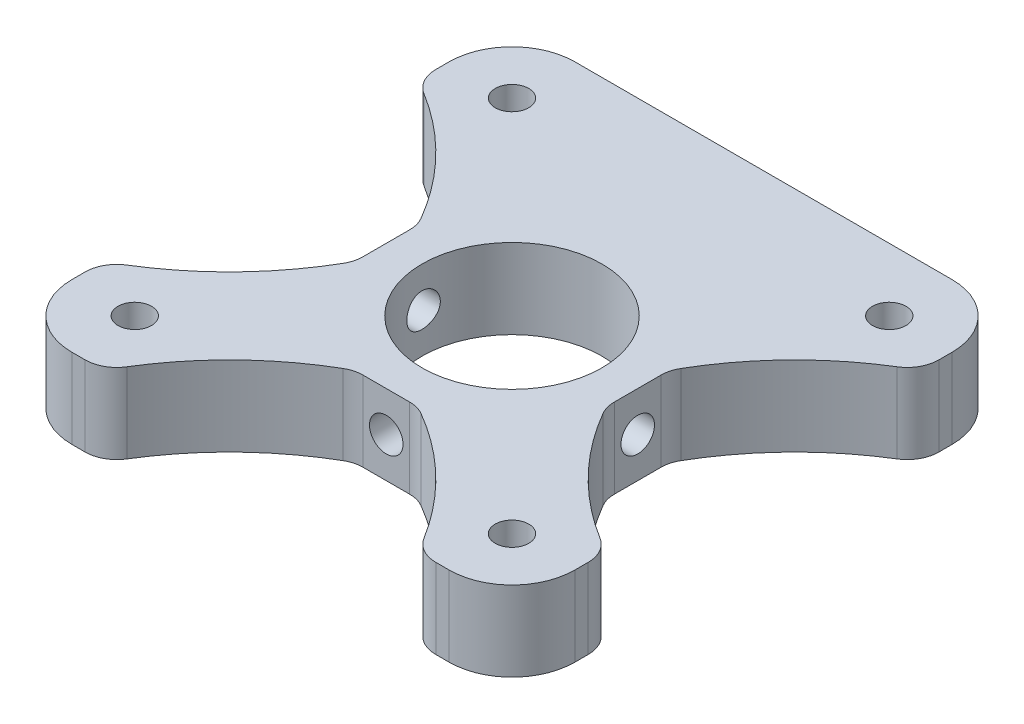
SolidWorks part; units mm, degrees
material "1060 Alloy"
ref_plane "Front Plane" through (0, 0, 0) normal (0, 0, 1) x (1, 0, 0)
ref_plane "Top Plane" through (0, 0, 0) normal (0, 1, 0) x (1, 0, 0)
ref_plane "Right Plane" through (0, 0, 0) normal (1, 0, 0) x (0, 0, -1)
sketch "Sketch1" plane through (0, 0, 0) normal (0, 1, 0) x (1, 0, 0)
  line L1 (-40, -40) -> (40, -40)
  line L2 (-40, -40) -> (-40, 40)
  line L3 (-40, 40) -> (40, 40)
  line L4 (40, -40) -> (40, 40)
  line L5 (-40, -40) -> (40, 40) construction
  line L6 (-40, 40) -> (40, -40) construction
  circle A0 centre (0, 0) radius 14.3129
  point P0 (0, 0)
  dimension "D1" = 28.6258
  dimension "D2" = 80
  dimension "D3" = 80
extrude "Boss-Extrude1" add sketch "Sketch1" along normal blind 12.7
fillet "Fillet1" radius 10 4 edges at (-40, 6.35, -40) (40, 6.35, -40) (40, 6.35, 40) (-40, 6.35, 40)
sketch "Sketch2" plane through (0, 12.7, 0) normal (0, 1, 0) x (1, 0, 0)
  line L0 (20, 40) -> (20, -40)
  line L1 (30, 40) -> (-30, 40) construction
  line L2 (-30, -40) -> (30, -40) construction
  line L3 (40, -30) -> (40, 30) construction
  line L4 (40, 0) -> (-40, 0) construction
  line L5 (-40, 30) -> (-40, -30) construction
  line L6 (40, -30) -> (40, 30)
  line L7 (40, 25) -> (40, -25)
  line L8 (20, 5) -> (20, -5)
  arc A0 (40, -25) -> (20, -5) centre (63.9116, 18.9116) cw
  arc A1 (30, -40) -> (40, -30) centre (30, -30) ccw construction
  arc A2 (40, 25) -> (20, 5) centre (63.9116, -18.9116) ccw
  point P11 (20, 0)
  point P16 (28.5563, -16.4437)
  dimension "D3" = 5
  dimension "D1" = 20
  dimension "D2" = 5
  dimension "D4" = 50
extrude "Cut-Extrude1" cut sketch "Sketch2" against normal up to next contours L4 L7 A2 L0 | L6 L4 L8 A0
mirror "Mirror1" about plane through (0, 0, 0) normal (1, 0, 0) of "Cut-Extrude1"
sketch "Sketch3" plane through (20, 0, 0) normal (1, 0, 0) x (0, 0, -1)
  line L0 (0, 12.7) -> (0, 0) construction
  line L1 (5, 12.7) -> (-5, 12.7) construction
  circle A0 centre (0, 6.35) radius 2.665
  dimension "D1" = 5.33
extrude "Cut-Extrude2" cut sketch "Sketch3" against normal up to next
fillet "Fillet2" radius 5 8 edges at (40, 6.35, -25) (40, 6.35, 25) (-40, 6.35, 25) (-40, 6.35, -25) (-20, 6.35, -5) (-20, 6.35, 5) (20, 6.35, 5) (20, 6.35, -5)
sketch "Sketch4" plane through (0, 12.7, 0) normal (0, 1, 0) x (1, 0, 0)
  circle A0 centre (-30, 30) radius 2.665
  circle A1 centre (30, 30) radius 2.665
  circle A2 centre (30, -30) radius 2.665
  circle A3 centre (-30, -30) radius 2.665
  dimension "D1" = 5.33
extrude "Cut-Extrude3" cut sketch "Sketch4" against normal up to next
pattern_circular "CirPattern1" count 3 every 90 about axis through (0, 0, 0) along (0, 1, 0) of "Cut-Extrude1"
fillet "Fillet3" radius 5 6 edges at (-5, 6.35, 20) (5, 6.35, 20) (25, 6.35, 40) (-25, 6.35, 40) (-20, 6.35, 5) (-20, 6.35, -5)
pattern_circular "CirPattern2" count 3 every 90 about axis through (0, 12.7, 0) along (0, 1, 0) of "Cut-Extrude2"
sketch "Sketch5" plane through (0, 0, -40) normal (0, 0, -1) x (-1, 0, 0)
  line L0 (16.75, 6.35) -> (30, 6.35) construction
  line L1 (30, 0) -> (30, 12.7) construction
  line L2 (16.75, 6.35) -> (-16.75, 6.35) construction
  line L3 (-16.75, 6.35) -> (-30, 6.35) construction
  line L4 (-30, 12.7) -> (-30, 0) construction
  circle A0 centre (-16.75, 6.35) radius 1.5 construction
  circle A1 centre (16.75, 6.35) radius 1.5 construction
  dimension "D2" = 3
  dimension "D1" = 33.5
hole_wizard "M5x0.8 Tapped Hole1" positions "3DSketch1" profile "Sketch6" tap size "M5x0.8" standard "ANSI Metric"
sketch3d "3DSketch1"
  point P0 (16.75, 6.35, -40)
  point P3 (-16.75, 6.35, -40)
sketch "Sketch6" plane through (16.75, 6.35, -40) normal (1, 0, 0) x (0, 1, 0)
  line L0 (0, 0) -> (0, 7.6118)
  line L1 (0, 7.6118) -> (2.1, 6.35)
  line L2 (2.1, 6.35) -> (2.1, 0)
  line L5 (2.1, 0) -> (0, 0)
  line L10 (0, 7.6118) -> (-2.1, 6.35) construction
  line L11 (0, -6.35) -> (0, 107.95) construction
  dimension "Tap Drill Dia." = 4.2
  dimension "Tap Drill Depth" = 6.35
  dimension "Drill Angle" = 118
cosmetic thread "Hole Thread1" parameters "D1"=6.35, "D2"=5
cosmetic thread "Hole Thread2" parameters "D1"=6.35, "D2"=5
